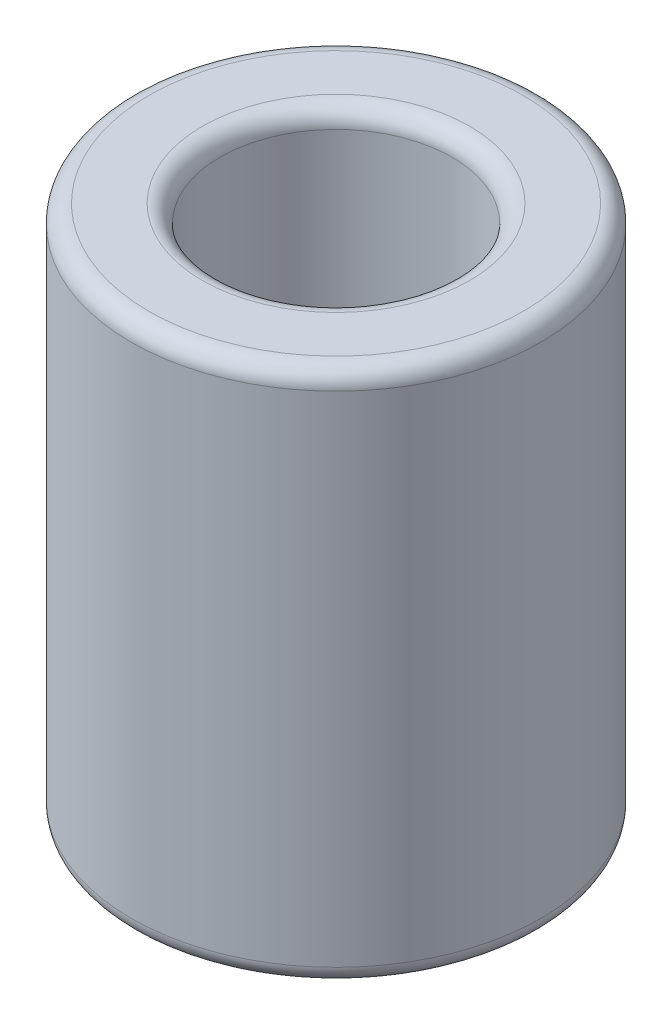
SolidWorks part; units mm, degrees
ref_plane "Front Plane" through (0, 0, 0) normal (0, 0, 1) x (1, 0, 0)
ref_plane "Top Plane" through (0, 0, 0) normal (0, 1, 0) x (1, 0, 0)
ref_plane "Right Plane" through (0, 0, 0) normal (1, 0, 0) x (0, 0, -1)
sketch "Sketch1" plane through (0, 0, 0) normal (0, 1, 0) x (1, 0, 0)
  circle A0 centre (0, 0) radius 11.5
  dimension "D1" = 23
extrude "Boss-Extrude1" add sketch "Sketch1" along normal blind 30
sketch "Sketch2" plane through (0, 30, 0) normal (0, 1, 0) x (1, 0, 0)
  circle A0 centre (0, 0) radius 6.5
  circle A1 centre (0, 0) radius 11.5 construction
  dimension "D1" = 5
extrude "Cut-Extrude1" cut sketch "Sketch2" against normal through all
fillet "Fillet2" radius 1 4 edges at (0, 0, 6.5) (0, 0, 11.5) (0, 30, 6.5) (0, 30, 11.5)
